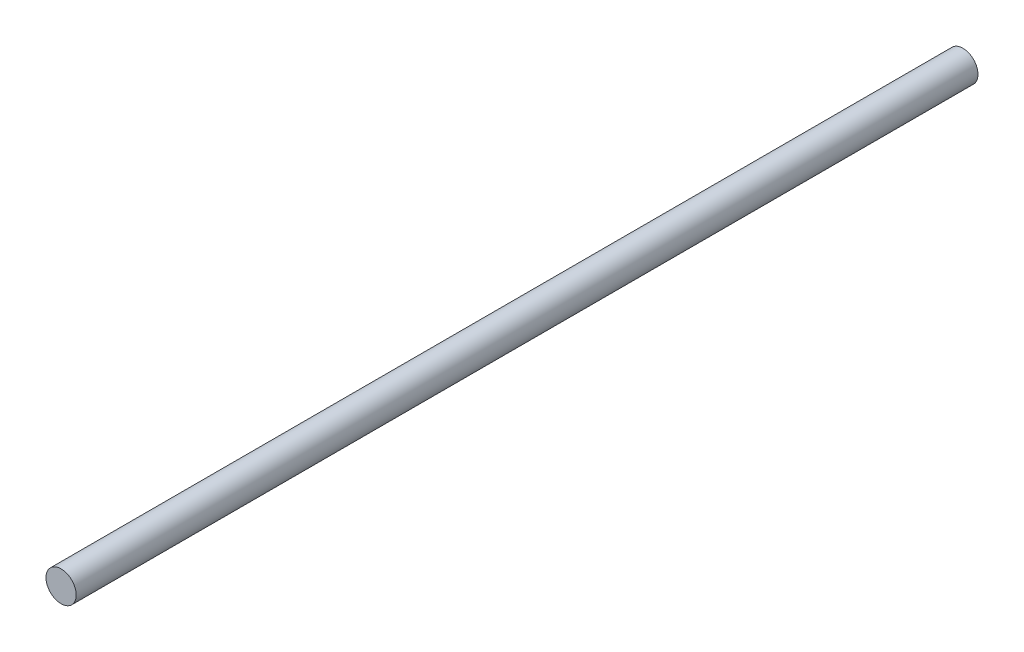
SolidWorks part; units mm, degrees
ref_plane "前视基准面" through (0, 0, 0) normal (0, 0, 1) x (1, 0, 0)
ref_plane "上视基准面" through (0, 0, 0) normal (0, 1, 0) x (1, 0, 0)
ref_plane "右视基准面" through (0, 0, 0) normal (1, 0, 0) x (0, 0, -1)
other "Configuration Table"
sketch "草图1" plane through (0, 0, 0) normal (0, 0, 1) x (1, 0, 0)
  circle A0 centre (0, 0) radius 2.5
extrude "凸台-拉伸1" add sketch "草图1" along normal blind 149.09
